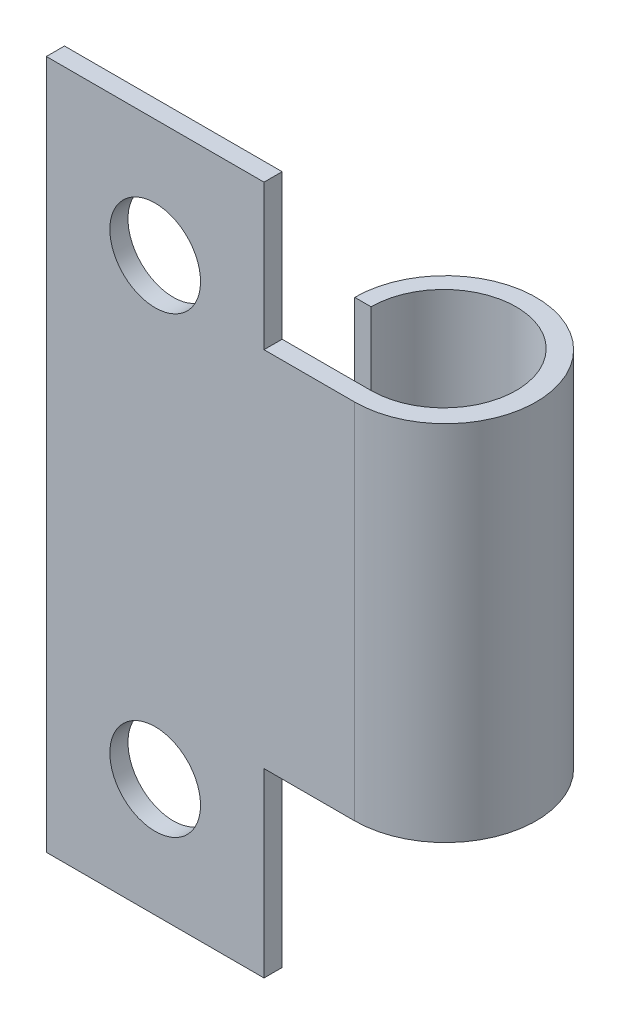
SolidWorks part; units mm, degrees
ref_plane "前视基准面" through (0, 0, 0) normal (0, 0, 1) x (1, 0, 0)
ref_plane "上视基准面" through (0, 0, 0) normal (0, 1, 0) x (1, 0, 0)
ref_plane "右视基准面" through (0, 0, 0) normal (1, 0, 0) x (0, 0, -1)
sketch "草图1" plane through (0, 0, 0) normal (0, 0, 1) x (1, 0, 0)
  line L0 (6, 38) -> (6, 0) construction
  line L1 (0, 0) -> (12, 0)
  line L2 (0, 0) -> (0, 38)
  line L3 (0, 38) -> (12, 38)
  line L4 (12, 0) -> (12, 38)
  circle A0 centre (6, 31.5) radius 2.5
  circle A1 centre (6, 6.5) radius 2.5
  dimension "D3" = 6.5
  dimension "D4" = 6.5
  dimension "D5" = 5
  dimension "D6" = 5
  dimension "D1" = 38
  dimension "D2" = 12
extrude "凸台-拉伸1" add sketch "草图1" along normal blind 1
ref_plane "基准面1" through (0, 30, 0) normal (0, 1, 0) x (1, 0, 0)
sketch "草图2" plane through (0, 30, 0) normal (0, 1, 0) x (1, 0, 0)
  line L0 (12, 0) -> (12, -1)
  line L1 (12, -1) -> (17, -1)
  line L2 (12, 4) -> (12.9028, 4)
  line L3 (16.9028, 0) -> (12, 0)
  arc A0 (17, -1) -> (12, 4) centre (17, 4) ccw
  arc A1 (12.9028, 4) -> (16.9028, 0) centre (16.9028, 4) cw
  dimension "D1" = 5
extrude "凸台-拉伸2" add sketch "草图2" against normal blind 20
